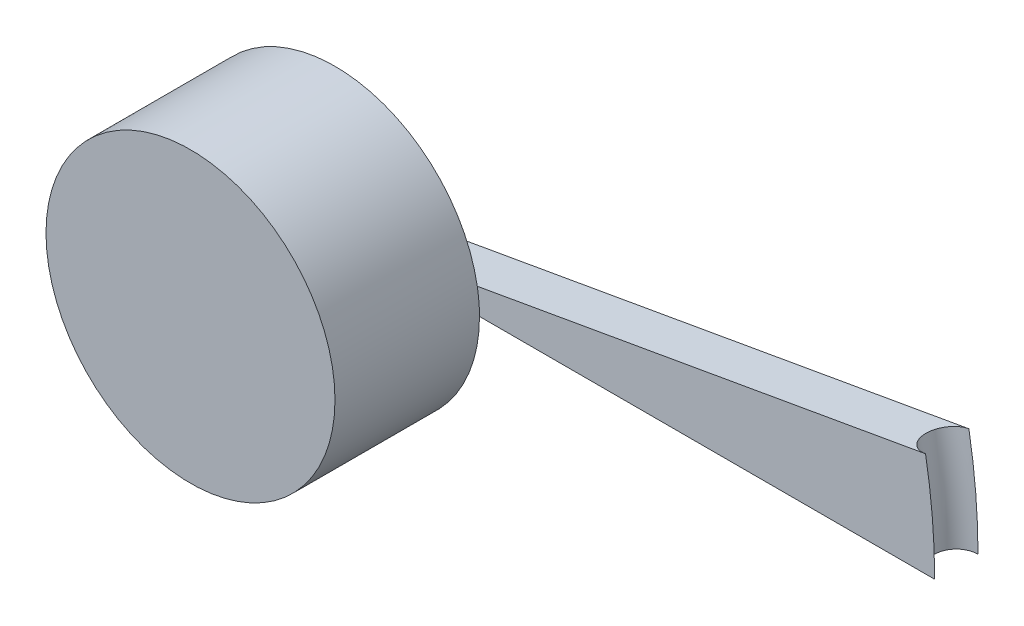
SolidWorks part; units mm, degrees
ref_plane "Front Plane" through (0, 0, 0) normal (0, 0, 1) x (1, 0, 0)
ref_plane "Top Plane" through (0, 0, 0) normal (0, 1, 0) x (1, 0, 0)
ref_plane "Right Plane" through (0, 0, 0) normal (1, 0, 0) x (0, 0, -1)
sketch "Sketch1" plane through (0, 0, 0) normal (0, 1, 0) x (1, 0, 0)
  line L0 (40, 1.5) -> (41.5, 1.5)
  line L1 (0, 1.5) -> (40, 1.5)
  line L2 (0, 1.5) -> (0, -1.5)
  line L3 (0, -1.5) -> (40, -1.5)
  line L4 (40, 1.5) -> (40, -1.5) construction
  line L7 (41.5, -1.5) -> (40, -1.5)
  arc A2 (41.5, 1.5) -> (41.5, -1.5) centre (41.5, 0) ccw
  point P4 (0, 0)
  dimension "D1" = 3
  dimension "D2" = 40
revolve "Revolve2" add sketch "Sketch1" angle 10 about L2
sketch "Sketch2" plane through (0, 0, 1.5) normal (0, 0, 1) x (1, 0, 0)
  circle A0 centre (0, 0) radius 10
  dimension "D1" = 20
extrude "Boss-Extrude1" add sketch "Sketch2" along normal blind 10
